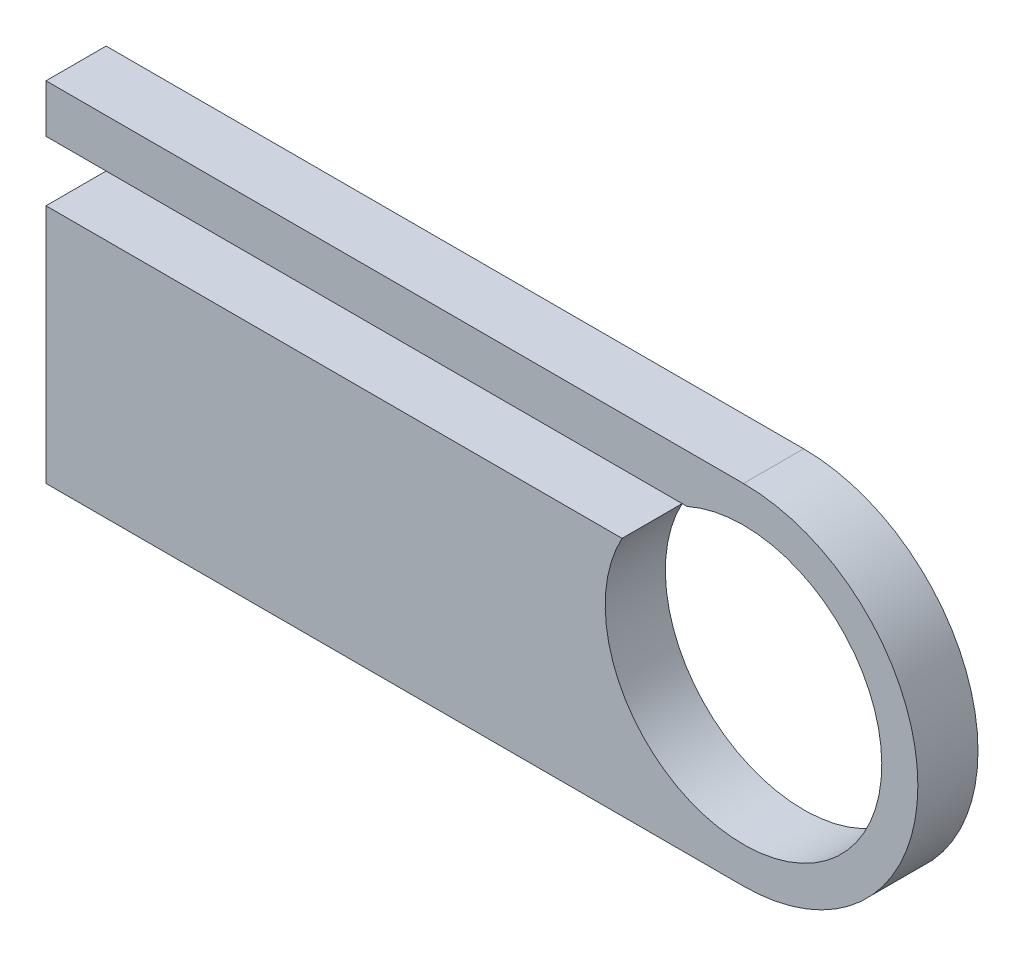
SolidWorks part; units mm, degrees
ref_plane "Front Plane" through (0, 0, 0) normal (0, 0, 1) x (1, 0, 0)
ref_plane "Top Plane" through (0, 0, 0) normal (0, 1, 0) x (1, 0, 0)
ref_plane "Right Plane" through (0, 0, 0) normal (1, 0, 0) x (0, 0, -1)
sketch "Sketch1" plane through (0, 0, 0) normal (0, 0, 1) x (1, 0, 0)
  line L0 (0, 0) -> (0, 4)
  line L2 (0, 0) -> (53.3096, 0)
  line L4 (47.9005, -5) -> (0, -5)
  line L5 (0, -5) -> (0, -25)
  line L6 (0, -25) -> (58, -25)
  line L9 (0, 4) -> (58, 4)
  arc A1 (58, 4) -> (58, -25) centre (58, -10.5) cw
  arc A4 (53.3096, 0) -> (47.9005, -5) centre (58, -10.5) cw
  dimension "D1" = 3
  dimension "D2" = 58
  dimension "D3" = 4
  dimension "D4" = 5
  dimension "D5" = 20
extrude "Boss-Extrude1" add sketch "Sketch1" along normal blind 5
